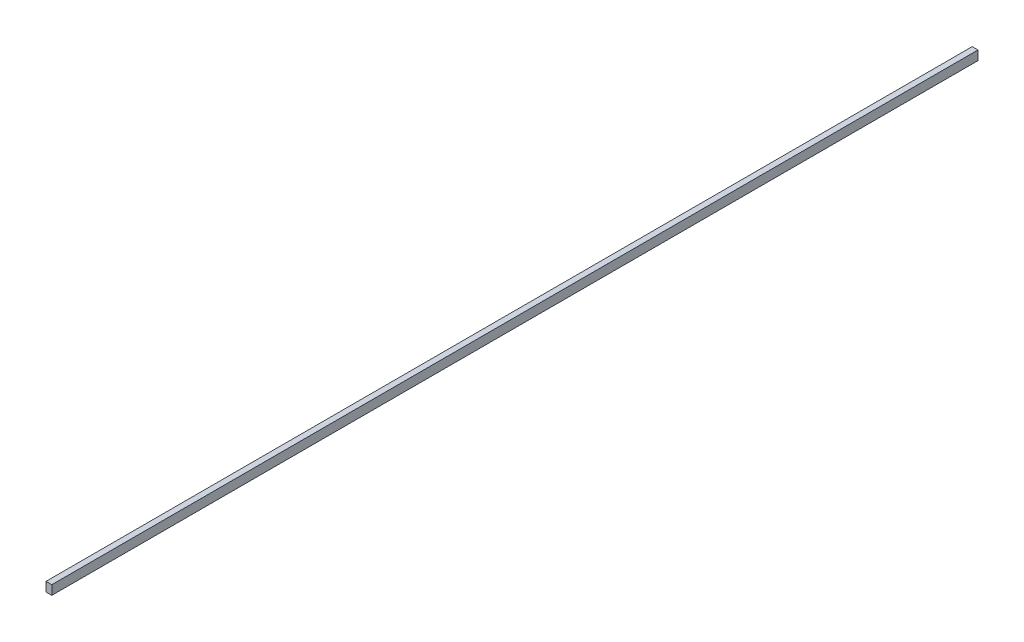
SolidWorks part; units mm, degrees
material "1060 Alloy"
ref_plane "Front Plane" through (0, 0, 0) normal (0, 0, 1) x (1, 0, 0)
ref_plane "Top Plane" through (0, 0, 0) normal (0, 1, 0) x (1, 0, 0)
ref_plane "Right Plane" through (0, 0, 0) normal (1, 0, 0) x (0, 0, -1)
sketch "Sketch1" plane through (0, 0, 0) normal (0, 0, 1) x (1, 0, 0)
  line L1 (-25, 40) -> (25, 40)
  line L2 (-25, 40) -> (-25, -40)
  line L3 (-25, -40) -> (25, -40)
  line L4 (25, 40) -> (25, -40)
  point P0 (0, 0)
  point P7 (0, 0)
  dimension "D1" = 80
  dimension "D2" = 50
extrude "Boss-Extrude1" add sketch "Sketch1" along normal blind 8000 contours L1 L4 L3 L2
sketch "Sketch2" plane through (0, 0, 0) normal (0, 0, -1) x (-1, 0, 0)
  line L1 (-21, 36) -> (21, 36)
  line L2 (-21, 36) -> (-21, -36)
  line L3 (-21, -36) -> (21, -36)
  line L4 (21, 36) -> (21, -36)
  line L5 (-21, 36) -> (21, -36) construction
  line L6 (-21, -36) -> (21, 36) construction
  point P0 (0, 0)
  dimension "D1" = 42
  dimension "D2" = 72
extrude "Cut-Extrude1" cut sketch "Sketch2" against normal blind 6000
